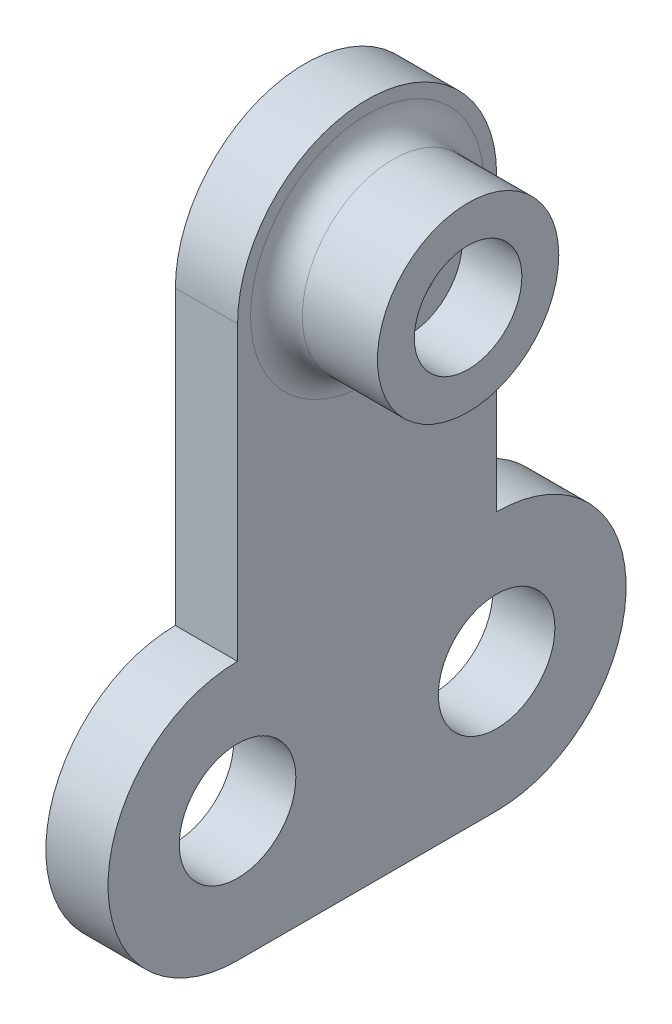
SolidWorks part; units mm, degrees
ref_plane "前视基准面" through (0, 0, 0) normal (0, 0, 1) x (1, 0, 0)
ref_plane "上视基准面" through (0, 0, 0) normal (0, 1, 0) x (1, 0, 0)
ref_plane "右视基准面" through (0, 0, 0) normal (1, 0, 0) x (0, 0, -1)
sketch "草图1" plane through (0, 0, 0) normal (1, 0, 0) x (0, 0, -1)
  line L0 (-5, 0) -> (5, 0)
  line L5 (-5, 10) -> (-5, 21.2822)
  line L6 (5, 10) -> (5, 21.2822)
  circle A2 centre (-5, 5) radius 2.25
  circle A3 centre (5, 5) radius 2.25
  arc A4 (-5, 10) -> (-5, 0) centre (-5, 5) ccw
  arc A6 (5, 0) -> (5, 10) centre (5, 5) ccw
  arc A10 (-5, 21.2822) -> (5, 21.2822) centre (0, 21.2822) cw
  circle A12 centre (0, 21.2822) radius 2.075
  dimension "D3" = 4.5
  dimension "D4" = 5
  dimension "D1" = 10
  dimension "D5" = 4.15
  dimension "D8" = 5
  dimension "D2" = 10
  dimension "D9" = 11.2822
extrude "凸台-拉伸1" add sketch "草图1" along normal blind 2.4
sketch "草图4" plane through (2.4, 0, 0) normal (1, 0, 0) x (0, 0, -1)
  circle A0 centre (0, 21.2822) radius 3.5
  circle A1 centre (0, 21.2822) radius 2.075 construction
  circle A2 centre (0, 21.2822) radius 2.075
  dimension "D1" = 7
extrude "凸台-拉伸2" add sketch "草图4" along normal blind 3.9
fillet "圆角1" radius 1 1 edges at (2.4, 21.2822, -3.5)
sketch "草图5" plane through (0, 0, 0) normal (-1, 0, 0) x (0, 0, 1)
  circle A0 centre (0, 21.2822) radius 1.2
  circle A1 centre (0, 21.2822) radius 2.075
extrude "凸台-拉伸3" add sketch "草图5" against normal blind 4
